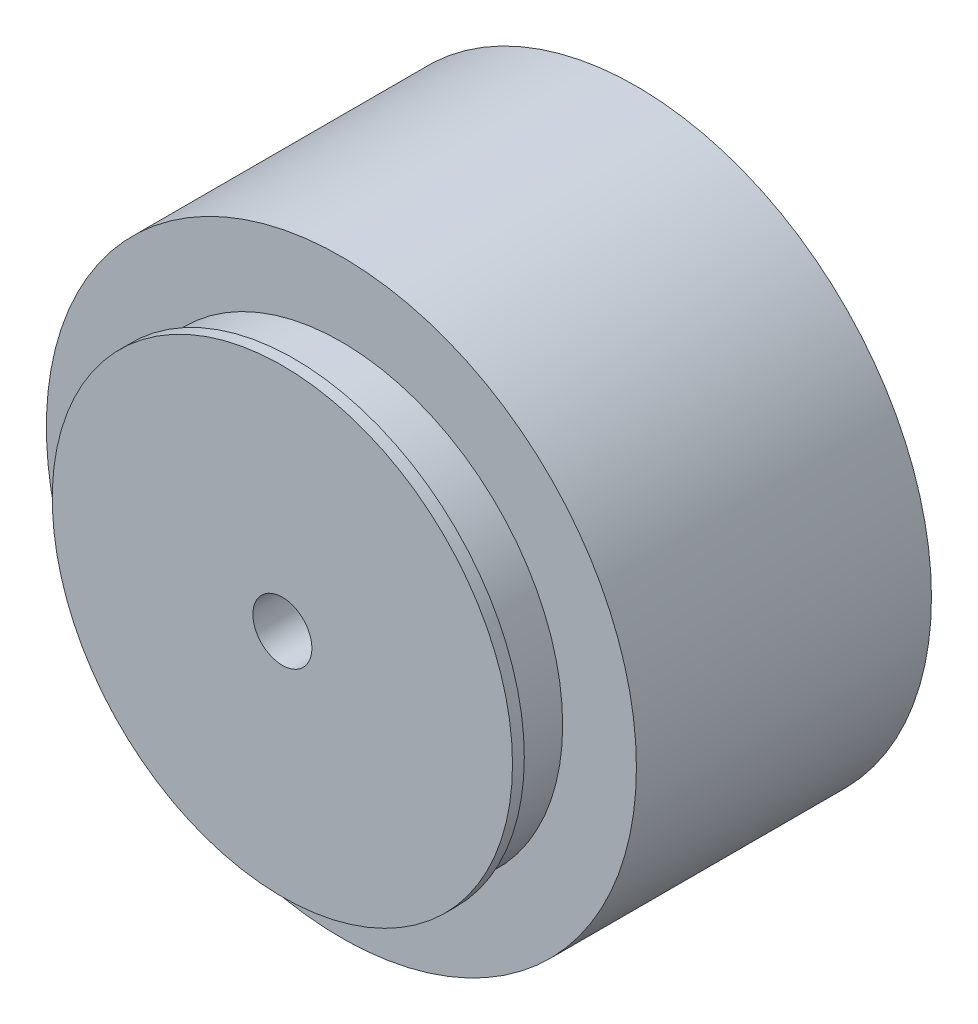
SolidWorks part; units mm, degrees
ref_plane "Front Plane" through (0, 0, 0) normal (0, 0, 1) x (1, 0, 0)
ref_plane "Top Plane" through (0, 0, 0) normal (0, 1, 0) x (1, 0, 0)
ref_plane "Right Plane" through (0, 0, 0) normal (1, 0, 0) x (0, 0, -1)
sketch "Sketch1" plane through (0, 0, 0) normal (0, 0, 1) x (1, 0, 0)
  circle A0 centre (0, 0) radius 50
  circle A1 centre (0, 0) radius 5
  dimension "D1" = 100
  dimension "D2" = 10
extrude "Boss-Extrude1" add sketch "Sketch1" along normal blind 50
sketch "Sketch2" plane through (0, 0, 50) normal (0, 0, 1) x (1, 0, 0)
  circle A0 centre (0, 0) radius 5 construction
  circle A1 centre (0, 0) radius 5
  circle A2 centre (0, 0) radius 37.5
  dimension "D1" = 75
extrude "Boss-Extrude2" add sketch "Sketch2" along normal blind 8
sketch "Sketch3" plane through (0, 0, 58) normal (0, 0, 1) x (1, 0, 0)
  circle A0 centre (0, 0) radius 5 construction
  circle A1 centre (0, 0) radius 5
  circle A2 centre (0, 0) radius 39
  dimension "D1" = 78
extrude "Boss-Extrude3" add sketch "Sketch3" along normal blind 2
sketch "Sketch4" plane through (0, 0, 0) normal (0, 0, -1) x (-1, 0, 0)
  circle A0 centre (0, 0) radius 15
  circle A1 centre (0, 0) radius 5 construction
  circle A2 centre (0, 0) radius 5
  dimension "D1" = 30
extrude "Boss-Extrude4" add sketch "Sketch4" along normal blind 10
